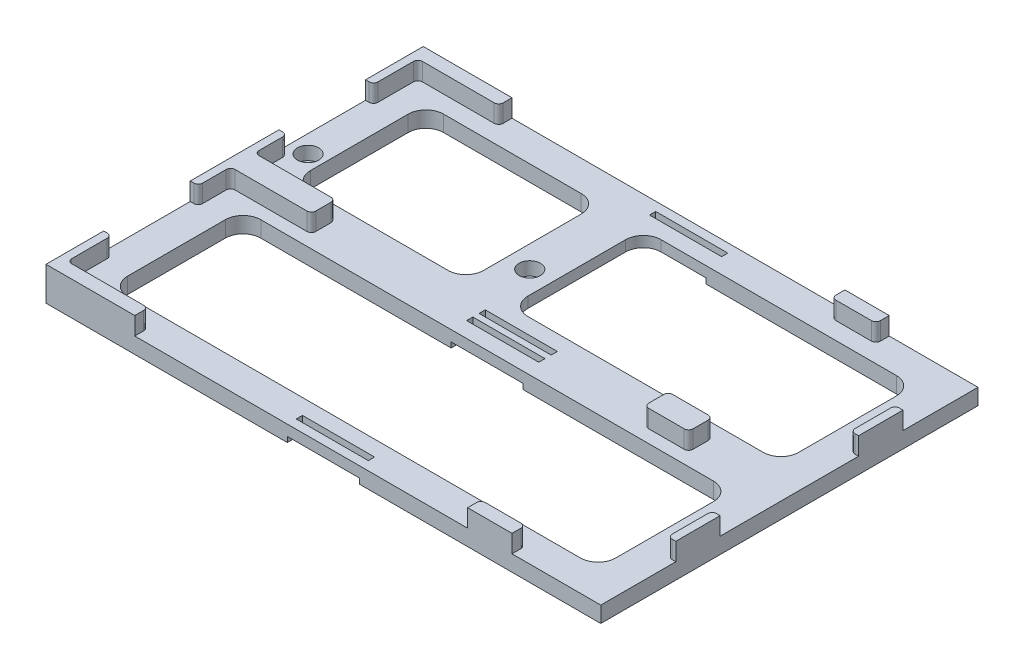
SolidWorks part; units mm, degrees
ref_plane "Front Plane" through (0, 0, 0) normal (0, 0, 1) x (1, 0, 0)
ref_plane "Top Plane" through (0, 0, 0) normal (0, 1, 0) x (1, 0, 0)
ref_plane "Right Plane" through (0, 0, 0) normal (1, 0, 0) x (0, 0, -1)
sketch "Sketch3" plane through (0, 0, 0) normal (0, 1, 0) x (1, 0, 0)
  line L1 (0, 0) -> (158.75, 0)
  line L2 (0, 0) -> (0, 107.95)
  line L3 (0, 107.95) -> (158.75, 107.95)
  line L4 (158.75, 0) -> (158.75, 107.95)
  dimension "D1" = 107.95
  dimension "D2" = 158.75
extrude "Base Extrude" add sketch "Sketch3" along normal blind 4.572
sketch "Sketch4" plane through (0, 4.572, 0) normal (0, 1, 0) x (1, 0, 0)
  line L0 (158.75, 107.95) -> (0, 107.95) construction
  line L1 (69.0562, 105.41) -> (89.6938, 105.41)
  line L2 (69.0562, 105.41) -> (69.0562, 103.632)
  line L3 (69.0562, 103.632) -> (89.6938, 103.632)
  line L4 (89.6938, 105.41) -> (89.6938, 103.632)
  line L5 (69.0562, 56.642) -> (89.6938, 56.642)
  line L6 (69.0562, 56.642) -> (69.0562, 54.864)
  line L7 (69.0562, 54.864) -> (89.6938, 54.864)
  line L8 (89.6938, 56.642) -> (89.6938, 54.864)
  line L9 (69.0563, 53.086) -> (89.6938, 53.086)
  line L10 (69.0563, 53.086) -> (69.0563, 51.308)
  line L11 (69.0563, 51.308) -> (89.6938, 51.308)
  line L12 (89.6938, 53.086) -> (89.6938, 51.308)
  line L13 (69.0563, 4.318) -> (89.6938, 4.318)
  line L14 (69.0563, 4.318) -> (69.0563, 2.54)
  line L15 (69.0563, 2.54) -> (89.6938, 2.54)
  line L16 (89.6938, 4.318) -> (89.6938, 2.54)
  line L17 (0, 0) -> (158.75, 0) construction
  line L18 (9.525, 46.863) -> (149.225, 46.863)
  line L19 (9.525, 99.187) -> (149.225, 99.187)
  line L20 (9.525, 99.187) -> (9.525, 61.087)
  line L21 (9.525, 61.087) -> (149.225, 61.087)
  line L22 (149.225, 99.187) -> (149.225, 61.087)
  line L23 (9.525, 46.863) -> (9.525, 8.763)
  line L24 (9.525, 8.763) -> (149.225, 8.763)
  line L25 (149.225, 46.863) -> (149.225, 8.763)
  line L26 (79.375, 103.632) -> (79.375, 56.642) construction
  line L27 (79.375, 51.308) -> (79.375, 4.318) construction
  point P28 (79.375, 105.41)
  point P29 (79.375, 107.95)
  point P32 (9.525, 80.137)
  point P33 (79.375, 80.137)
  point P34 (9.525, 27.813)
  point P35 (79.375, 99.187)
  point P36 (79.375, 27.813)
  point P40 (79.375, 46.863)
  dimension "D1" = 46.99
  dimension "D2" = 46.99
  dimension "D3" = 1.778
  dimension "D4" = 20.6375
  dimension "D5" = 2.54
  dimension "D6" = 2.54
  dimension "D7" = 38.1
  dimension "D8" = 139.7
extrude "Velcro slits" cut sketch "Sketch4" against normal through all
sketch "Sketch6" plane through (0, 4.572, 0) normal (0, 1, 0) x (1, 0, 0)
  line L0 (2.286, 16.51) -> (2.286, 3.81)
  line L1 (2.286, 3.81) -> (25.4, 3.81)
  line L2 (25.4, 3.81) -> (25.4, 0)
  line L3 (25.4, 0) -> (0, 0)
  line L4 (0, 0) -> (0, 16.51)
  line L5 (0, 16.51) -> (2.286, 16.51)
  line L6 (2.286, 41.275) -> (2.286, 50.546)
  line L7 (2.286, 50.546) -> (25.4, 50.546)
  line L8 (25.4, 50.546) -> (25.4, 57.404)
  line L9 (25.4, 57.404) -> (2.286, 57.404)
  line L10 (2.286, 57.404) -> (2.286, 66.675)
  line L11 (2.286, 66.675) -> (0, 66.675)
  line L12 (0, 66.675) -> (0, 41.275)
  line L13 (0, 41.275) -> (2.286, 41.275)
  line L14 (0, 91.44) -> (2.286, 91.44)
  line L15 (2.286, 91.44) -> (2.286, 104.14)
  line L19 (0, 107.95) -> (0, 91.44)
  line L20 (79.375, 61.087) -> (79.375, 46.863) construction
  line L21 (9.525, 61.087) -> (149.225, 61.087) construction
  line L22 (149.225, 46.863) -> (9.525, 46.863) construction
  line L23 (79.375, 103.632) -> (79.375, 56.642) construction
  line L28 (69.0562, 103.632) -> (89.6938, 103.632) construction
  line L29 (89.6938, 56.642) -> (69.0562, 56.642) construction
  line L34 (79.375, 51.308) -> (79.375, 4.318) construction
  line L35 (69.0563, 51.308) -> (89.6938, 51.308) construction
  line L36 (89.6938, 4.318) -> (69.0563, 4.318) construction
  line L37 (0, 107.95) -> (0, 0) construction
  line L38 (0, 0) -> (158.75, 0) construction
  line L39 (2.286, 104.14) -> (25.4, 104.14)
  line L40 (25.4, 104.14) -> (25.4, 107.95)
  line L41 (25.4, 107.95) -> (0, 107.95)
  line L42 (158.75, 107.95) -> (0, 107.95) construction
  line L43 (158.75, 0) -> (158.75, 107.95) construction
  line L44 (158.75, 86.487) -> (156.464, 86.487)
  line L45 (158.75, 86.487) -> (158.75, 73.787)
  line L46 (158.75, 73.787) -> (156.464, 73.787)
  line L47 (156.464, 86.487) -> (156.464, 73.787)
  line L49 (158.75, 34.163) -> (156.464, 34.163)
  line L50 (158.75, 34.163) -> (158.75, 21.463)
  line L51 (158.75, 21.463) -> (156.464, 21.463)
  line L52 (156.464, 34.163) -> (156.464, 21.463)
  line L53 (133.35, 107.95) -> (120.65, 107.95)
  line L54 (133.35, 107.95) -> (133.35, 104.14)
  line L55 (133.35, 104.14) -> (120.65, 104.14)
  line L56 (120.65, 107.95) -> (120.65, 104.14)
  line L57 (120.65, 57.404) -> (133.35, 57.404)
  line L58 (120.65, 57.404) -> (120.65, 50.546)
  line L59 (120.65, 50.546) -> (133.35, 50.546)
  line L60 (133.35, 57.404) -> (133.35, 50.546)
  line L61 (133.35, 3.81) -> (120.65, 3.81)
  line L62 (133.35, 3.81) -> (133.35, 0)
  line L63 (133.35, 0) -> (120.65, 0)
  line L64 (120.65, 3.81) -> (120.65, 0)
  point P26 (25.4, 53.975)
  point P27 (79.375, 53.975)
  point P39 (3.175, 80.137)
  point P40 (79.375, 80.137)
  point P41 (79.375, 27.813)
  point P47 (3.175, 27.305)
  point P54 (155.575, 27.813)
  point P71 (156.464, 80.137)
  point P72 (156.464, 27.813)
  point P85 (120.65, 53.975)
  dimension "D1" = 2.286
  dimension "D2" = 12.7
  dimension "D5" = 25.4
  dimension "D6" = 6.858
  dimension "D7" = 3.81
  dimension "D8" = 25.4
  dimension "D9" = 2.286
  dimension "D10" = 12.7
  dimension "D11" = 12.7
  dimension "D12" = 25.4
extrude "Position Guides" add sketch "Sketch6" along normal blind 5.08
fillet "Fillet1" radius 1.27 24 edges at (156.464, 7.112, -21.463) (156.464, 7.112, -34.163) (156.464, 7.112, -73.787) (156.464, 7.112, -86.487) (120.65, 7.112, -3.81) (133.35, 7.112, -3.81) (133.35, 7.112, -104.14) (120.65, 7.112, -104.14) (120.65, 7.112, -50.546) (120.65, 7.112, -57.404) (133.35, 7.112, -57.404) (133.35, 7.112, -50.546) (2.286, 7.112, -66.675) (2.286, 7.112, -57.404) (25.4, 7.112, -3.81) (2.286, 7.112, -3.81) (2.286, 7.112, -16.51) (25.4, 7.112, -50.546) (25.4, 7.112, -57.404) (2.286, 7.112, -41.275) (2.286, 7.112, -50.546) (25.4, 7.112, -104.14) (2.286, 7.112, -104.14) (2.286, 7.112, -91.44)
sketch "Sketch7" plane through (0, 4.572, 0) normal (0, 1, 0) x (1, 0, 0)
  line L0 (0, 91.44) -> (0, 66.675) construction
  line L1 (120.65, 107.95) -> (25.4, 107.95) construction
  line L5 (9.525, 61.087) -> (149.225, 61.087) construction
  line L8 (59.055, 99.187) -> (59.055, 61.087)
  line L9 (149.225, 99.187) -> (9.525, 99.187) construction
  line L10 (59.055, 61.087) -> (71.755, 61.087)
  line L11 (71.755, 61.087) -> (71.755, 99.187)
  line L12 (71.755, 99.187) -> (59.055, 99.187)
  circle A0 centre (5.08, 69.85) radius 1.905
  circle A1 centre (65.405, 73.025) radius 1.905
  point P4 (65.405, 99.187)
  dimension "D3" = 3.81
  dimension "D1" = 60.325
  dimension "D2" = 3.175
  dimension "D4" = 5.08
  dimension "D5" = 38.1
  dimension "D7" = 12.7
extrude "Right screw hole and support" add sketch "Sketch7" against normal up to surface (4.572 mm away) up to face at (79.375, 0, -104.521)
sketch "Sketch10" plane through (0, 4.572, 0) normal (0, 1, 0) x (1, 0, 0)
  circle A0 centre (5.08, 69.9135) radius 1.905
  circle A1 centre (65.405, 73.025) radius 1.905 construction
  dimension "D1" = 3.81
  dimension "D2" = 60.325
  dimension "D3" = 3.1115
extrude "Left Screw Hole" cut sketch "Sketch10" against normal through all
fillet "Fillet2" radius 5.08 12 edges at (71.755, 2.286, -61.087) (9.525, 2.286, -8.763) (59.055, 2.286, -61.087) (149.225, 2.286, -61.087) (149.225, 2.286, -8.763) (149.225, 2.286, -46.863) (149.225, 2.286, -99.187) (59.055, 2.286, -99.187) (71.755, 2.286, -99.187) (9.525, 2.286, -46.863) (9.525, 2.286, -99.187) (9.525, 2.286, -61.087)
sketch "Sketch11" plane through (0, 4.572, 0) normal (0, 1, 0) x (1, 0, 0)
  circle A0 centre (5.08, 69.9135) radius 3.048
  circle A1 centre (65.405, 73.025) radius 3.048
  dimension "D1" = 6.096
extrude "Screwhead cutouts" cut sketch "Sketch11" against normal blind 3.81
sketch "Sketch5" plane through (0, 0, 0) normal (0, 0, 1) x (1, 0, 0)
  line L1 (69.0563, 1.524) -> (89.6938, 1.524)
  line L2 (69.0563, 1.524) -> (69.0563, 0)
  line L3 (69.0563, 0) -> (89.6938, 0)
  line L4 (89.6938, 1.524) -> (89.6938, 0)
  line L5 (89.6938, 0) -> (89.6938, 4.572) construction
  line L6 (0, 0) -> (158.75, 0) construction
  line L7 (69.0563, 0) -> (69.0563, 4.572) construction
  dimension "D1" = 1.524
extrude "Cut-Extrude1" cut sketch "Sketch5" against normal through all
